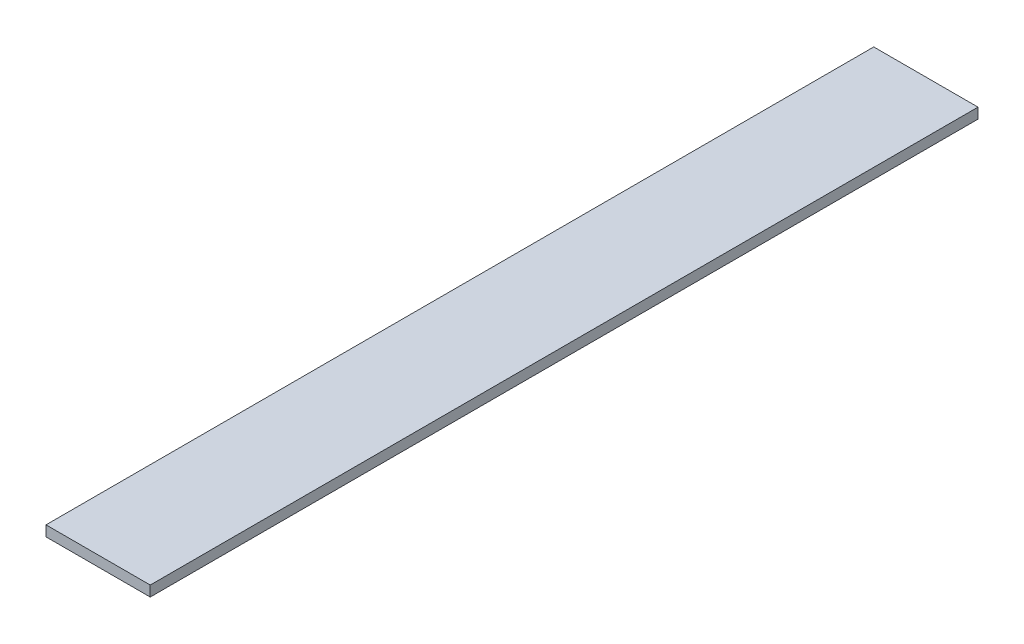
SolidWorks part; units mm, degrees
ref_plane "Front Plane" through (0, 0, 0) normal (0, 0, 1) x (1, 0, 0)
ref_plane "Top Plane" through (0, 0, 0) normal (0, 1, 0) x (1, 0, 0)
ref_plane "Right Plane" through (0, 0, 0) normal (1, 0, 0) x (0, 0, -1)
sketch "Sketch1" plane through (0, 0, 0) normal (0, 1, 0) x (1, 0, 0)
  line L1 (465, 277.5) -> (-465, 277.5)
  line L2 (465, 277.5) -> (465, -277.5)
  line L3 (465, -277.5) -> (-465, -277.5)
  line L4 (-465, 277.5) -> (-465, -277.5)
  line L5 (465, 277.5) -> (-465, -277.5) construction
  line L6 (465, -277.5) -> (-465, 277.5) construction
  line L7 (401.5, 252.1) -> (-401.5, 252.1)
  line L8 (401.5, 252.1) -> (401.5, -252.1)
  line L9 (401.5, -252.1) -> (-401.5, -252.1)
  line L10 (-401.5, 252.1) -> (-401.5, -252.1)
  line L11 (401.5, 252.1) -> (-401.5, -252.1) construction
  line L12 (401.5, -252.1) -> (-401.5, 252.1) construction
  point P0 (0, 0)
  point P6 (0, 0)
  dimension "D1" = 63.5
  dimension "D2" = 555
  dimension "D3" = 25.4
  dimension "D4" = 930
extrude "Boss-Extrude2" add sketch "Sketch1" along normal blind 6.35
sketch "Sketch2" plane through (0, 6.35, 0) normal (0, 1, 0) x (1, 0, 0)
  line L7 (-465, 277.5) -> (426.9, 277.5)
  line L8 (-465, 277.5) -> (-465, 252.1)
  line L9 (-465, 252.1) -> (401.5, 252.1)
  line L11 (-465, 277.5) -> (-465, -277.5) construction
  line L12 (-465, -252.1) -> (401.5, -252.1)
  line L13 (-465, -252.1) -> (-465, -277.5)
  line L14 (-465, -277.5) -> (426.9, -277.5)
  line L16 (-401.5, -252.1) -> (401.5, -252.1) construction
  line L18 (401.5, 252.1) -> (401.5, -252.1)
  line L21 (401.5, 252.1) -> (-401.5, 252.1) construction
  line L22 (401.5, -252.1) -> (401.5, 252.1) construction
  line L23 (426.9, 277.5) -> (465, 277.5)
  line L24 (465, 277.5) -> (465, -277.5)
  line L25 (465, -277.5) -> (426.9, -277.5)
extrude "Cut-Extrude1" cut sketch "Sketch2" against normal through all both and the other way through all
